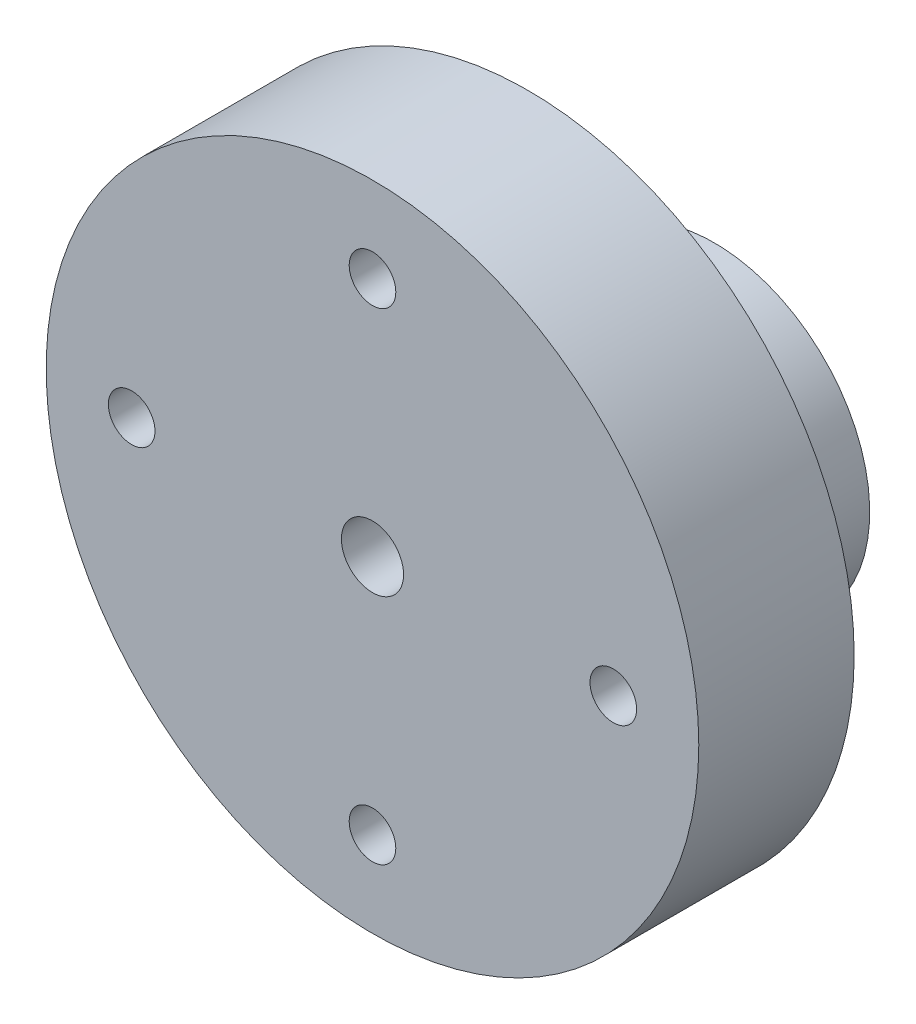
SolidWorks part; units mm, degrees
ref_plane "前视基准面" through (0, 0, 0) normal (0, 0, 1) x (1, 0, 0)
ref_plane "上视基准面" through (0, 0, 0) normal (0, 1, 0) x (1, 0, 0)
ref_plane "右视基准面" through (0, 0, 0) normal (1, 0, 0) x (0, 0, -1)
sketch "草图1" plane through (0, 0, 0) normal (0, 0, 1) x (1, 0, 0)
  line L0 (0, 0) -> (0, -3.5) construction
  circle A0 centre (0, 0) radius 21
  circle A1 centre (0, 0) radius 15.5 construction
  circle A2 centre (0, -15.5) radius 1.5
  circle A3 centre (-15.5, 0) radius 1.5
  circle A4 centre (0, 15.5) radius 1.5
  circle A5 centre (15.5, 0) radius 1.5
  circle A6 centre (0, 0) radius 2
  circle A7 centre (0, -3.5) radius 14 construction
  circle A8 centre (0, -3.5) radius 10 construction
  dimension "D1" = 42
  dimension "D2" = 31
  dimension "D3" = 3
  dimension "D5" = 4
  dimension "D7" = 28
  dimension "D8" = 20
  dimension "D6" = 3.5
  dimension "D4" = 4
extrude "凸台-拉伸1" add sketch "草图1" along normal blind 10 contours A0 | A4 | A3 | A5 | A2
sketch "草图2" plane through (0, 0, 0) normal (0, 0, -1) x (-1, 0, 0)
  line L0 (0, 0) -> (0, -3.5) construction
  circle A0 centre (0, -3.5) radius 14
  dimension "D2" = 28
  dimension "D1" = 3.5
extrude "凸台-拉伸2" add sketch "草图2" along normal blind 3.5
sketch "草图3" plane through (0, 0, -3.5) normal (0, 0, -1) x (-1, 0, 0)
  circle A0 centre (0, -3.5) radius 10
  dimension "D1" = 20
extrude "凸台-拉伸3" add sketch "草图3" along normal blind 8.5
sketch "草图4" plane through (0, 0, -12) normal (0, 0, -1) x (-1, 0, 0)
  line L0 (0, 0) -> (-6.5, 0) construction
  line L1 (0, 0) -> (0, 2.3278) construction
  circle A0 centre (-6.5, 0) radius 1.4
  circle A1 centre (6.5, 0) radius 1.4
  dimension "D2" = 2.8
  dimension "D1" = 6.5
sketch "草图5" plane through (0, 0, 10) normal (0, 0, 1) x (1, 0, 0)
  circle A0 centre (0, 0) radius 2
extrude "切除-拉伸1" cut sketch "草图5" against normal blind 28
extrude "切除-拉伸2" cut sketch "草图4" against normal blind 9.5
sketch "草图6" plane through (0, 0, 0) normal (0, 0, -1) x (-1, 0, 0)
  circle A0 centre (0, 15.5) radius 4
  circle A1 centre (15.5, 0) radius 4
  circle A2 centre (0, -15.5) radius 4
  circle A3 centre (-15.5, 0) radius 4
  dimension "D1" = 8
extrude "切除-拉伸3" cut sketch "草图6" against normal blind 5.5 and the other way blind 15.5
sketch "草图7" plane through (0, 0, -12) normal (0, 0, -1) x (-1, 0, 0)
  line L0 (0, 0) -> (0, 3.5) construction
  circle A1 centre (0, 3.5) radius 11.25
  dimension "D1" = 3.5
extrude "切除-拉伸5" [suppressed] cut sketch "草图7" against normal blind 1.5 contours A1
